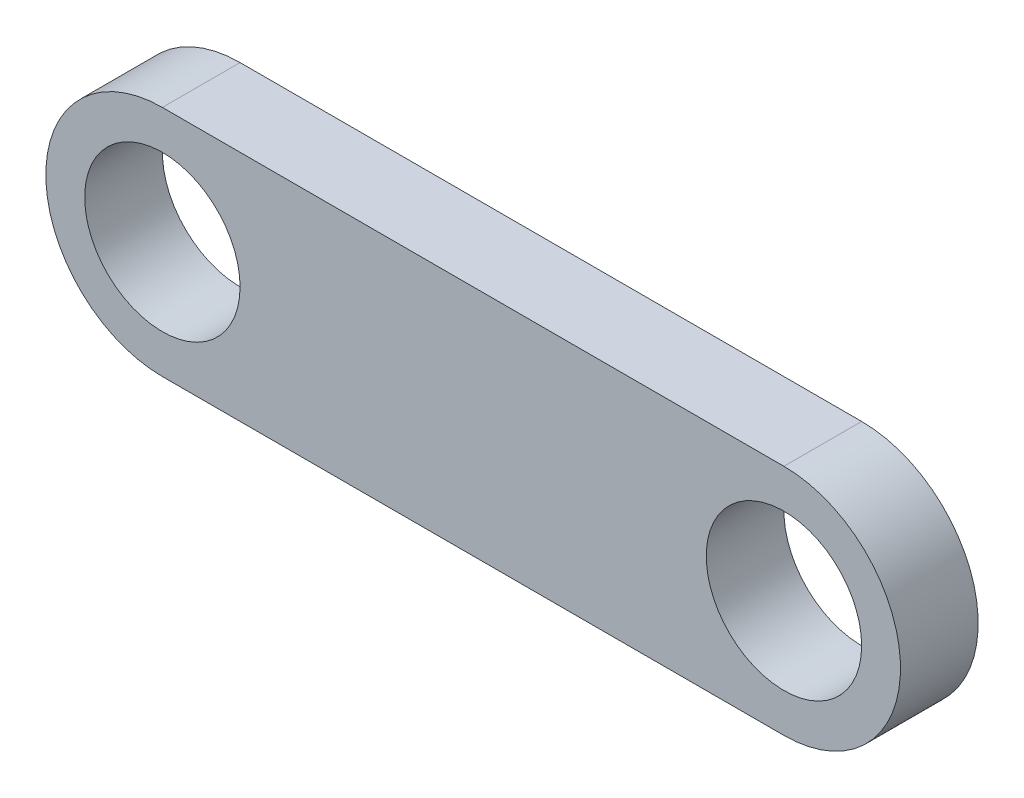
SolidWorks part; units mm, degrees
ref_plane "前视基准面" through (0, 0, 0) normal (0, 0, 1) x (1, 0, 0)
ref_plane "上视基准面" through (0, 0, 0) normal (0, 1, 0) x (1, 0, 0)
ref_plane "右视基准面" through (0, 0, 0) normal (1, 0, 0) x (0, 0, -1)
sketch "草图1" plane through (0, 0, 0) normal (0, 0, 1) x (1, 0, 0)
  line L0 (0, 0) -> (80, 0) construction
  line L1 (0, 15) -> (80, 15)
  line L2 (0, -15) -> (80, -15)
  arc A0 (0, 15) -> (0, -15) centre (0, 0) ccw
  arc A1 (80, -15) -> (80, 15) centre (80, 0) ccw
  circle A2 centre (0, 0) radius 10
  circle A3 centre (80, 0) radius 10
  point P3 (40, 0)
  dimension "D3" = 20
  dimension "D4" = 20
  dimension "D1" = 80
  dimension "D2" = 30
extrude "凸台-拉伸1" add sketch "草图1" along normal blind 10
